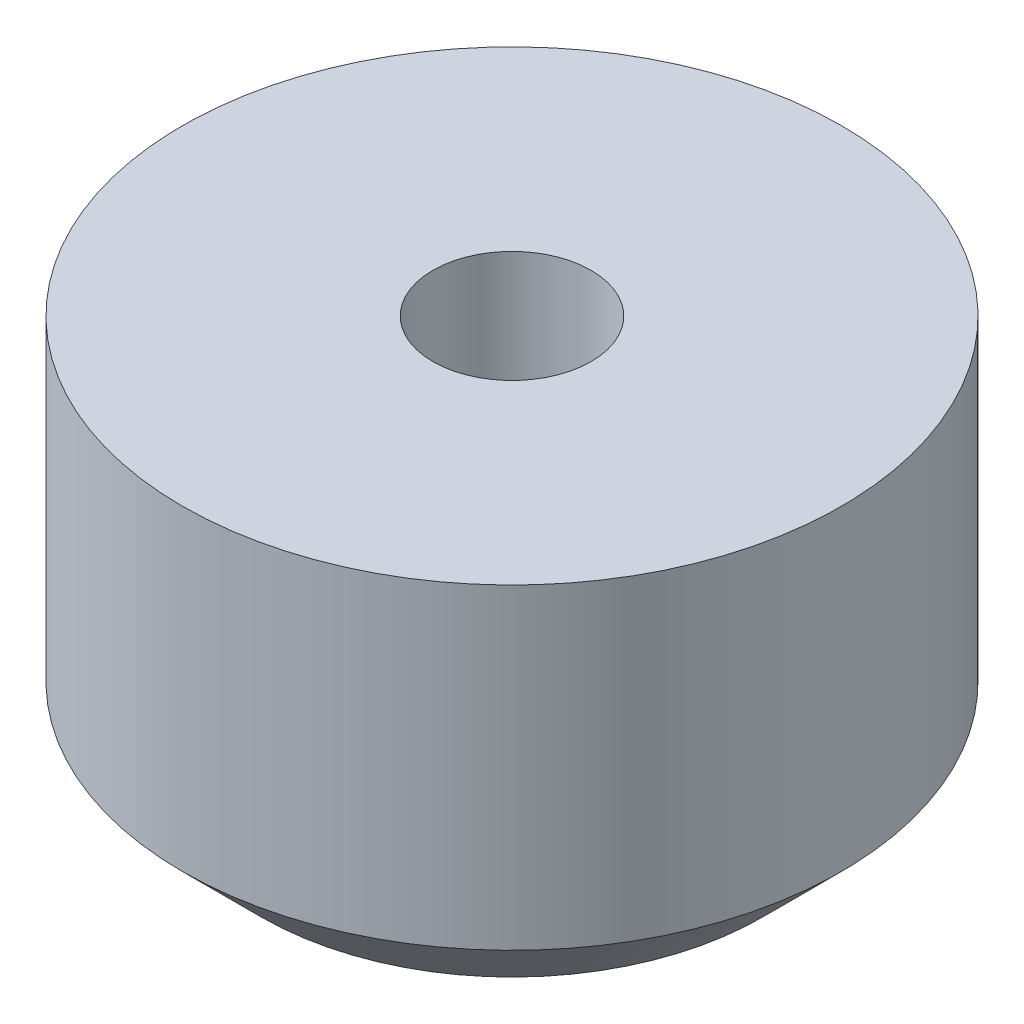
SolidWorks part; units mm, degrees
material "Rubber"
ref_plane "Front Plane" through (0, 0, 0) normal (0, 0, 1) x (1, 0, 0)
ref_plane "Top Plane" through (0, 0, 0) normal (0, 1, 0) x (1, 0, 0)
ref_plane "Right Plane" through (0, 0, 0) normal (1, 0, 0) x (0, 0, -1)
sketch "Sketch1" plane through (0, 0, 0) normal (0, 1, 0) x (1, 0, 0)
  circle A0 centre (0, 0) radius 12.5
  circle A1 centre (0, 0) radius 3
  dimension "D1" = 6
  dimension "D2" = 25
extrude "Boss-Extrude1" add sketch "Sketch1" along normal blind 15
chamfer "Chamfer1" distance 3 angle 45 1 edges at (0, 0, 12.5)
sketch "Sketch2" plane through (0, 0, 0) normal (0, -1, 0) x (1, 0, 0)
  circle A0 centre (0, 0) radius 6
  dimension "D1" = 12
extrude "Cut-Extrude1" cut sketch "Sketch2" against normal blind 5
